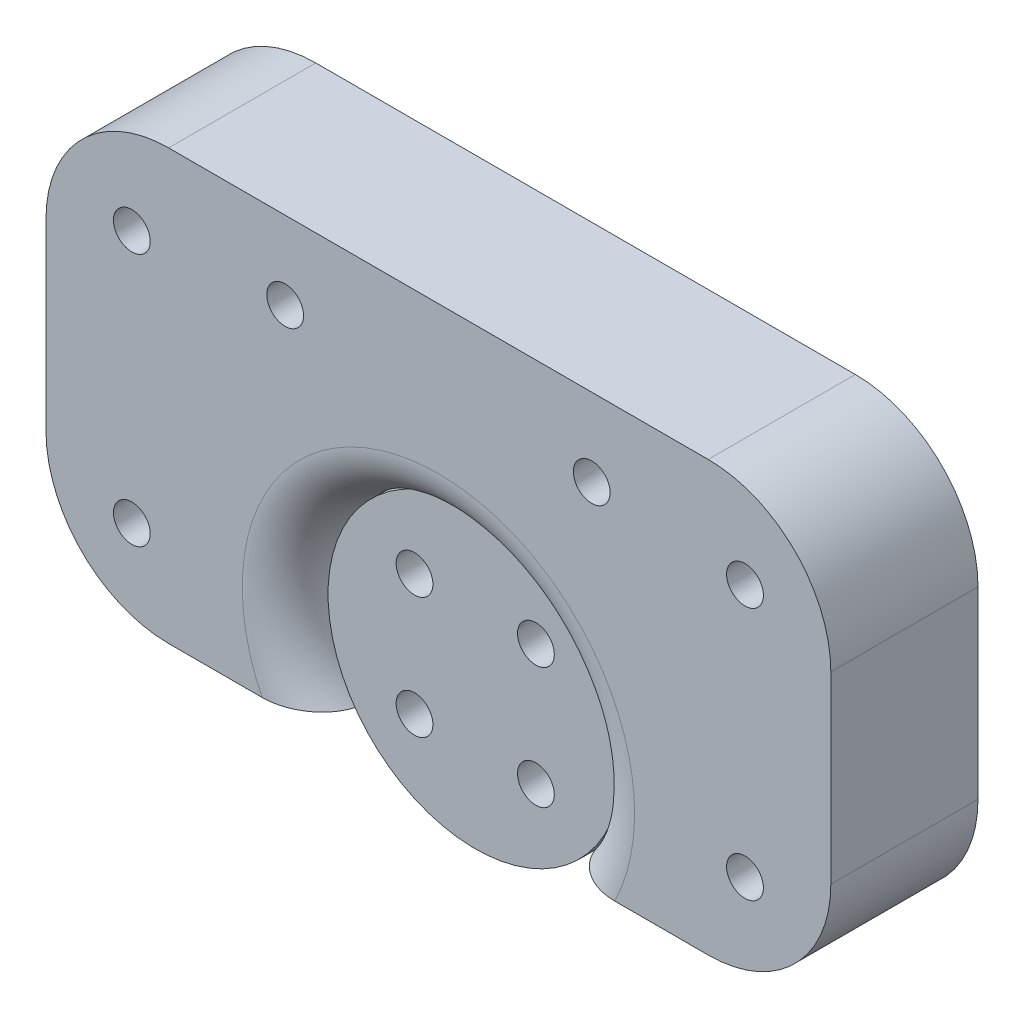
SolidWorks part; units mm, degrees
ref_plane "前视基准面" through (0, 0, 0) normal (0, 0, 1) x (1, 0, 0)
ref_plane "上视基准面" through (0, 0, 0) normal (0, 1, 0) x (1, 0, 0)
ref_plane "右视基准面" through (0, 0, 0) normal (1, 0, 0) x (0, 0, -1)
sketch "草图1" plane through (0, 0, 0) normal (0, 0, 1) x (1, 0, 0)
  line L5 (-4.9497, -4.9497) -> (4.9497, 4.9497) construction
  line L6 (-4.9497, 4.9497) -> (4.9497, -4.9497) construction
  circle A0 centre (0, 0) radius 12
  circle A6 centre (-4.9497, 4.9497) radius 1.5
  circle A7 centre (4.9497, 4.9497) radius 1.5
  circle A8 centre (-4.9497, -4.9497) radius 1.5
  circle A9 centre (4.9497, -4.9497) radius 1.5
extrude "凸台-拉伸1" add sketch "草图1" along normal blind 9
sketch "草图2" plane through (0, 0, 0) normal (0, 0, -1) x (-1, 0, 0)
  line L0 (-18, -7) -> (-32, -7)
  line L2 (-32, -7) -> (-32, 28)
  line L3 (-32, 28) -> (32, 28)
  line L4 (32, -7) -> (32, 28)
  line L9 (18, -7) -> (32, -7)
  line L11 (-18, -7) -> (-9.7435, -7)
  line L12 (18, -7) -> (9.7435, -7)
  circle A0 centre (-12.5, 21.65) radius 1.5
  circle A1 centre (12.5, 21.65) radius 1.5
  circle A2 centre (-25, 20.65) radius 1.5
  circle A3 centre (25, 20.65) radius 1.5
  circle A4 centre (-25, 0) radius 1.5
  circle A5 centre (25, 0) radius 1.5
  arc A6 (-9.7435, -7) -> (9.7435, -7) centre (0, 0) cw
  point P4 (0, 0)
  point P12 (0, 20.65)
  point P14 (0, 21.65)
extrude "凸台-拉伸2" add sketch "草图2" against normal blind 12 separate body
fillet "圆角2" radius 4 1 edges at (0, 11.9973, 12)
fillet "圆角3" radius 10 4 edges at (32, 28, 6) (32, -7, 6) (-32, 28, 6) (-32, -7, 6)
